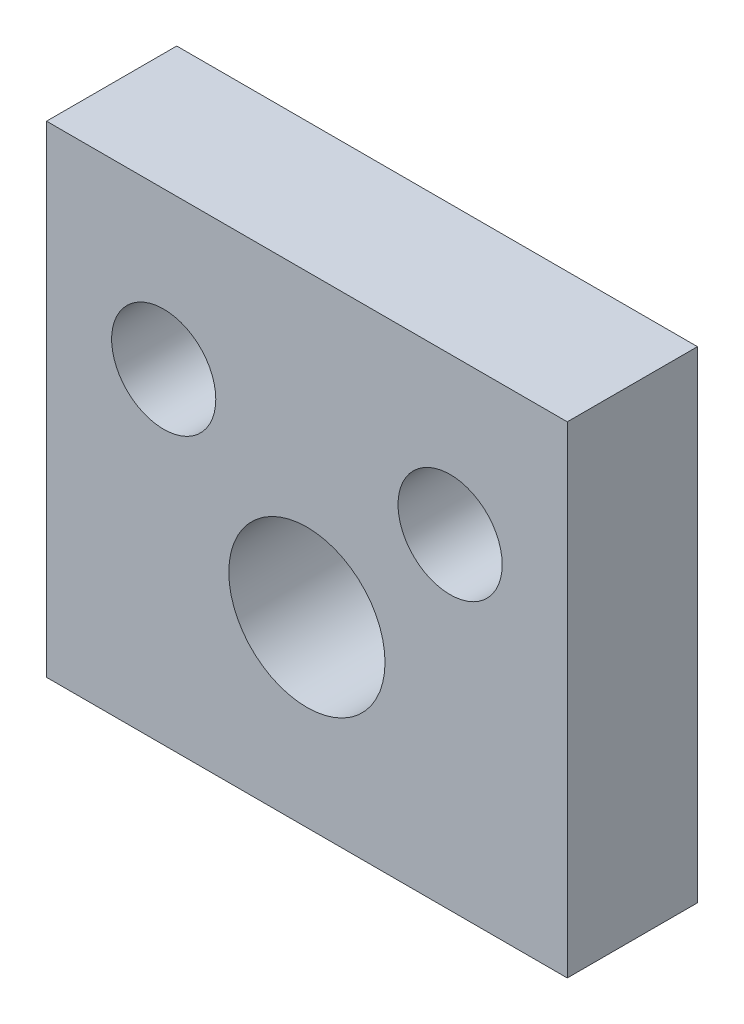
SolidWorks part; units mm, degrees
ref_plane "Plan de face" through (0, 0, 0) normal (0, 0, 1) x (1, 0, 0)
ref_plane "Plan de dessus" through (0, 0, 0) normal (0, 1, 0) x (1, 0, 0)
ref_plane "Plan de droite" through (0, 0, 0) normal (1, 0, 0) x (0, 0, -1)
sketch "Esquisse1" plane through (0, 0, 0) normal (0, 0, 1) x (1, 0, 0)
  line L1 (-13.5682, 7.432) -> (6.4318, 7.432)
  line L2 (-13.5682, 7.432) -> (-13.5682, -11.068)
  line L3 (-13.5682, -11.068) -> (6.4318, -11.068)
  line L4 (6.4318, 7.432) -> (6.4318, -11.068)
  line L5 (-3.5682, 7.432) -> (-3.5682, -11.068) construction
  circle A0 centre (-3.5682, -4.068) radius 3
  circle A1 centre (-9.0682, 1.432) radius 2
  circle A2 centre (1.9318, 1.432) radius 2
  dimension "D3" = 4.5
  dimension "D5" = 7
  dimension "D6" = 6
  dimension "D1" = 18.5
  dimension "D2" = 20
  dimension "D4" = 4.5
extrude "Extrusion1" add sketch "Esquisse1" along normal blind 5
